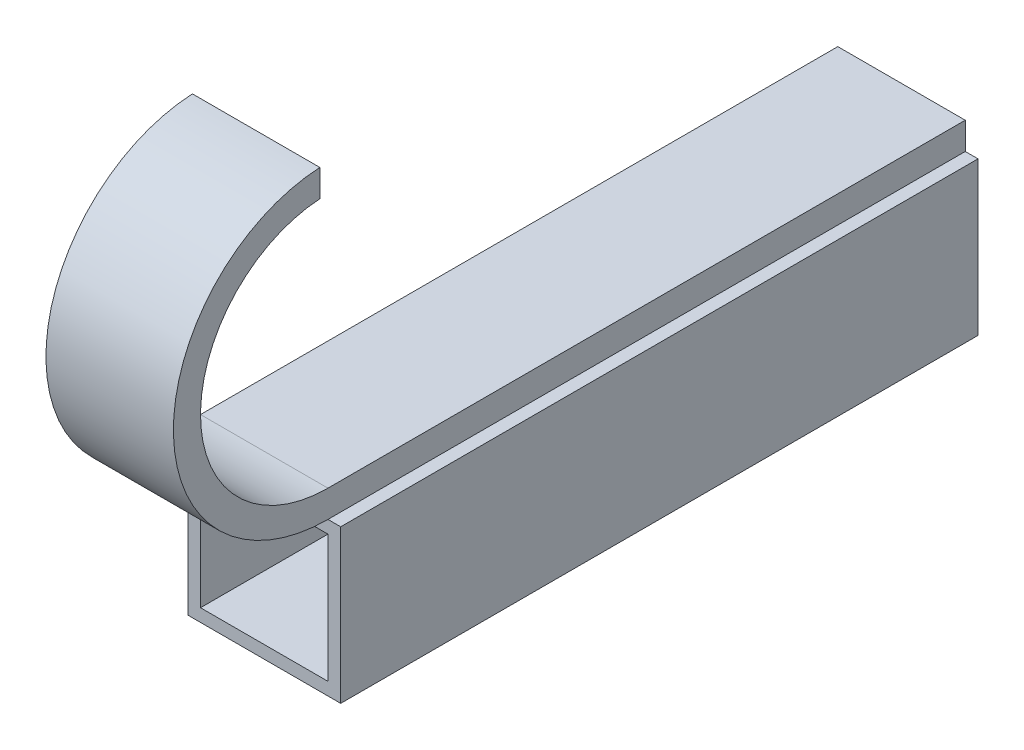
SolidWorks part; units mm, degrees
ref_plane "Front Plane" through (0, 0, 0) normal (0, 0, 1) x (1, 0, 0)
ref_plane "Top Plane" through (0, 0, 0) normal (0, 1, 0) x (1, 0, 0)
ref_plane "Right Plane" through (0, 0, 0) normal (1, 0, 0) x (0, 0, -1)
sketch "Sketch1" plane through (0, 0, 0) normal (0, 0, 1) x (1, 0, 0)
  line L0 (-2.54, -2.54) -> (-2.54, 27.94)
  line L1 (0, 0) -> (25.4, 0)
  line L2 (0, 0) -> (0, 25.4)
  line L3 (0, 25.4) -> (25.4, 25.4)
  line L4 (25.4, 0) -> (25.4, 25.4)
  line L5 (-2.54, 27.94) -> (27.94, 27.94)
  line L6 (27.94, -2.54) -> (27.94, 27.94)
  line L7 (-2.54, -2.54) -> (27.94, -2.54)
  dimension "D1" = 25.4
  dimension "D2" = 25.4
  dimension "D3" = 2.54
extrude "Boss-Extrude1" add sketch "Sketch1" along normal blind 127
ref_plane "Plane1" through (12.7, 0, 0) normal (1, 0, 0) x (0, 0, -1)
sketch "Sketch2" plane through (12.7, 0, 0) normal (1, 0, 0) x (0, 0, -1)
  line L0 (-127, 27.94) -> (0, 27.94) construction
  line L1 (0, 27.94) -> (0, 33.3385)
  line L2 (0, 33.3385) -> (-127, 33.3385)
  line L3 (-128.6147, 84.0871) -> (-128.6147, 89.4947)
  line L4 (-127, 27.94) -> (0, 27.94)
  line L5 (0, -2.54) -> (0, 27.94) construction
  arc A0 (-127, 33.3385) -> (-128.6147, 84.0871) centre (-127, 58.7385) cw
  arc A1 (-128.6147, 89.4947) -> (-127, 27.94) centre (-127, 58.7385) ccw
  point P11 (0, 0)
  point P12 (0, 0)
  point P14 (0, 0)
  point P15 (-120.646, 90.5102)
  point P16 (0, 0)
  point P17 (0, 0)
  dimension "D1" = 25.4
  dimension "D3" = 128.6147
  dimension "D2" = 5.3985
extrude "Boss-Extrude2" add sketch "Sketch2" along normal mid plane 25.4
